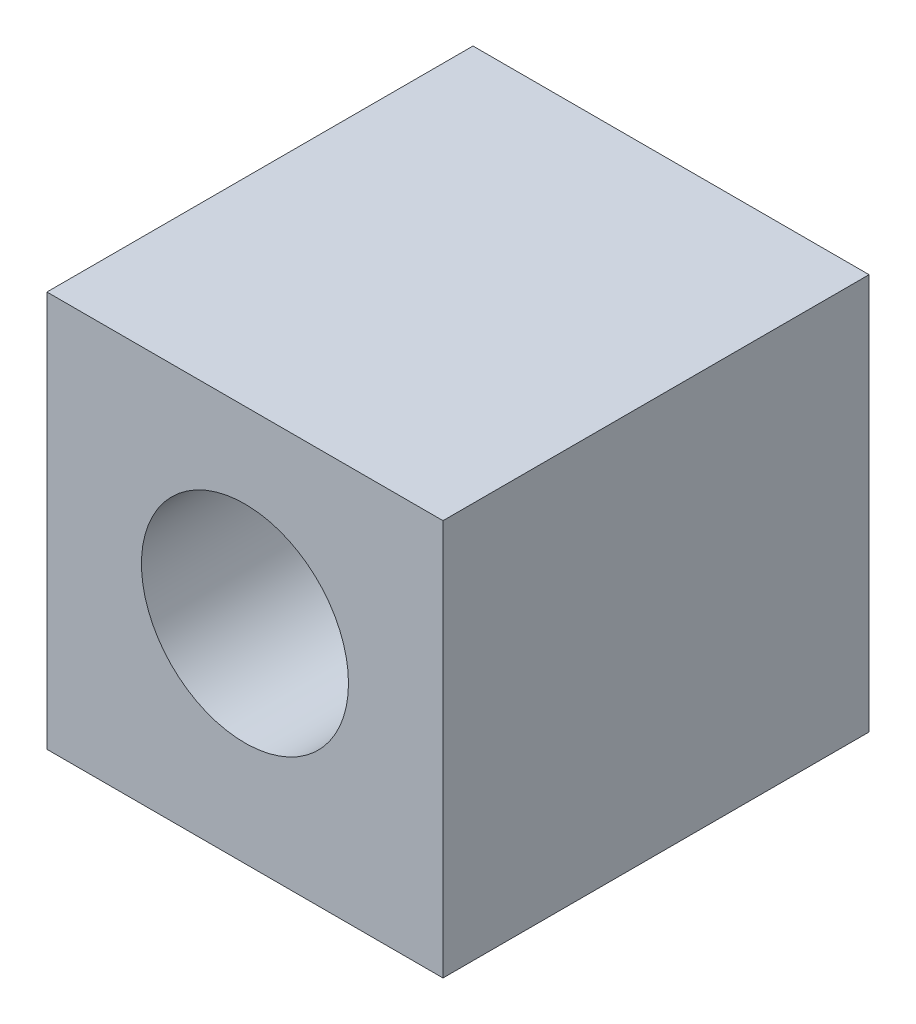
SolidWorks part; units mm, degrees
ref_plane "Plan de face" through (0, 0, 0) normal (0, 0, 1) x (1, 0, 0)
ref_plane "Plan de dessus" through (0, 0, 0) normal (0, 1, 0) x (1, 0, 0)
ref_plane "Plan de droite" through (0, 0, 0) normal (1, 0, 0) x (0, 0, -1)
sketch "Esquisse1" plane through (0, 0, 0) normal (0, 0, 1) x (1, 0, 0)
  line L1 (0, 0) -> (132, 0)
  line L2 (0, 0) -> (0, 132)
  line L3 (0, 132) -> (132, 132)
  line L4 (132, 0) -> (132, 132)
  dimension "D1" = 132
  dimension "D2" = 132
extrude "Boss.-Extru.1" add sketch "Esquisse1" along normal blind 142 contours L2 L1 L4 L3
sketch "Esquisse2" plane through (0, 0, 142) normal (0, 0, 1) x (1, 0, 0)
  line L0 (0, 0) -> (0, 132) construction
  circle A0 centre (66, 69.3269) radius 34.5
  point P4 (0, 0)
  dimension "D1" = 66
extrude "Enlèv. mat.-Extru.1" cut sketch "Esquisse2" against normal blind 142
